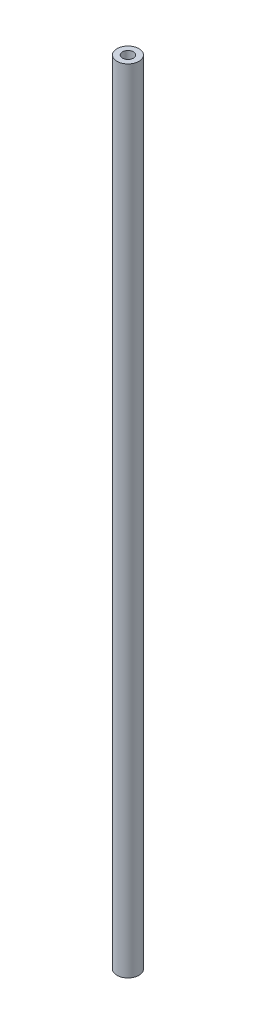
SolidWorks part; units mm, degrees
ref_plane "Front Plane" through (0, 0, 0) normal (0, 0, 1) x (1, 0, 0)
ref_plane "Top Plane" through (0, 0, 0) normal (0, 1, 0) x (1, 0, 0)
ref_plane "Right Plane" through (0, 0, 0) normal (1, 0, 0) x (0, 0, -1)
sketch "Sketch1" plane through (0, 0, 0) normal (0, 1, 0) x (1, 0, 0)
  circle A0 centre (0, 0) radius 12.7
  circle A1 centre (0, 0) radius 6.35
  dimension "D1" = 25.4
  dimension "D2" = 6.35
extrude "Boss-Extrude1" add sketch "Sketch1" along normal blind 914.4
equation "\"Pstrut_L\"= 36in"
equation "\"Pstrut_D\"= 1in"
equation "\"Pstrut_T\"= 0.25"
equation "\"Sstrut_L\"= 36in"
equation "\"Sstrut_D\"= 0.5in"
equation "\"Sstrut_T\"= 0.25"
equation "\"Dstrut_L\"= 10in"
equation "\"Dstrut_D\"= 0.5in"
equation "\"Dstrut_T\"= 0.25"
equation "\"D1@Sketch1\"=\"Pstrut_D\""
equation "\"D2@Sketch1\"=\"Dstrut_T\""
equation "\"D1@Boss-Extrude1\"=\"Pstrut_L\""
